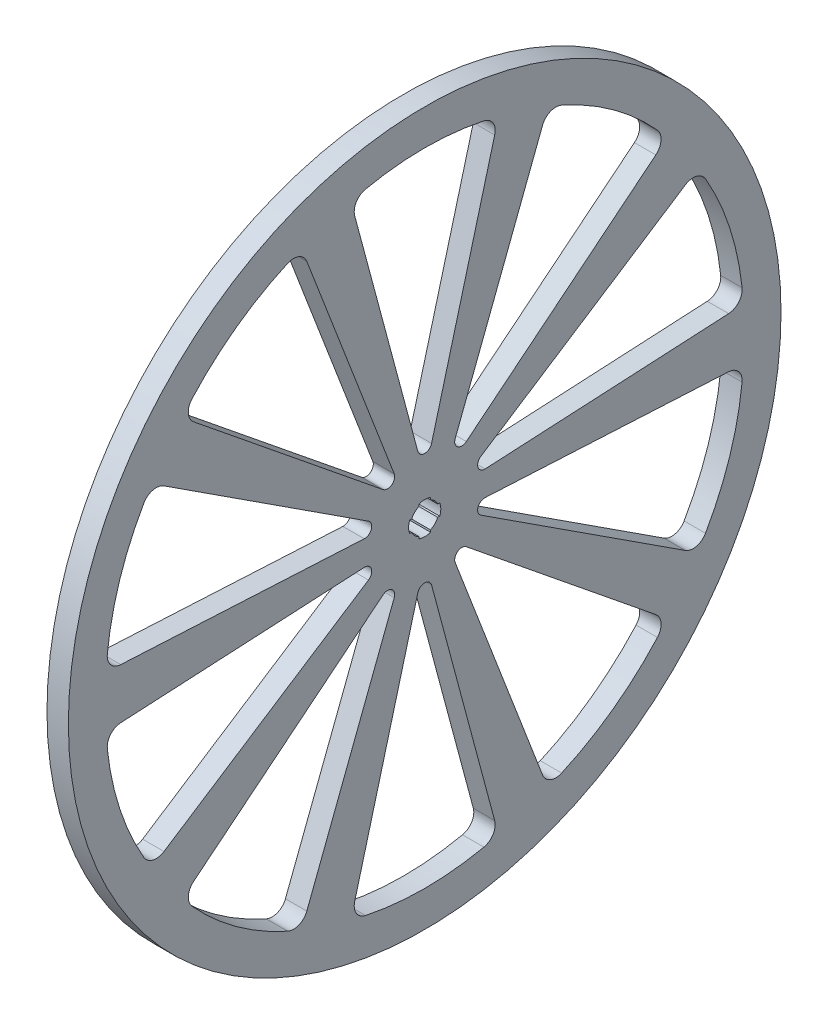
SolidWorks part; units mm, degrees
ref_plane "Front Plane" through (0, 0, 0) normal (0, 0, 1) x (1, 0, 0)
ref_plane "Top Plane" through (0, 0, 0) normal (0, 1, 0) x (1, 0, 0)
ref_plane "Right Plane" through (0, 0, 0) normal (1, 0, 0) x (0, 0, -1)
sketch "Sketch1" plane through (0, 0, 0) normal (1, 0, 0) x (0, 0, -1)
  circle A0 centre (0, 0) radius 50
  dimension "D1" = 100
extrude "Boss-Extrude1" add sketch "Sketch1" along normal blind 3
sketch "Sketch2" plane through (3, 0, 0) normal (1, 0, 0) x (0, 0, -1)
  circle A0 centre (0, 0) radius 2
  dimension "D1" = 4
extrude "Cut-Extrude1" cut sketch "Sketch2" against normal blind 3
sketch "Sketch3" plane through (3, 0, 0) normal (1, 0, 0) x (0, 0, -1)
  line L0 (0, 5) -> (0, 45) construction
  line L1 (0.9659, 8.6049) -> (9.8215, 41.6543)
  line L2 (-0.9659, 8.6049) -> (-9.8215, 41.6543)
  circle A0 centre (0, 0) radius 50 construction
  arc A2 (8.3049, 44.1284) -> (-8.3049, 44.1284) centre (0, 5) ccw
  arc A3 (9.8215, 41.6543) -> (8.3049, 44.1284) centre (7.8896, 42.1719) ccw
  arc A4 (-9.8215, 41.6543) -> (-8.3049, 44.1284) centre (-7.8896, 42.1719) cw
  arc A5 (-0.9659, 8.6049) -> (0.9659, 8.6049) centre (0, 8.8637) ccw
  point P11 (10.3528, 43.637)
  point P14 (-10.3528, 43.637)
  dimension "D7" = 2
  dimension "D8" = 1
  dimension "D1" = 5
  dimension "D2" = 45
  dimension "D3" = 15
  dimension "D4" = 40
  dimension "D5" = 15
  dimension "D6" = 40
extrude "Cut-Extrude2" cut sketch "Sketch3" against normal blind 3
pattern_circular "CirPattern2" count 10 over 360 about axis through (0, 0, 0) along (1, 0, 0) of "Cut-Extrude2"
sketch "Sketch4" plane through (3, 0, 0) normal (1, 0, 0) x (0, 0, -1)
  line L0 (-2.1099, 0.81) -> (-0.81, 0.81)
  line L1 (2.1099, -0.81) -> (-2.1099, -0.81) construction
  line L2 (2.1099, -0.81) -> (2.1099, 0.81) construction
  line L3 (2.1099, 0.81) -> (-2.1099, 0.81) construction
  line L4 (-2.1099, -0.81) -> (-2.1099, 0.81) construction
  line L5 (2.1099, -0.81) -> (-2.1099, 0.81) construction
  line L6 (2.1099, 0.81) -> (-2.1099, -0.81) construction
  line L7 (-0.81, -2.1099) -> (0.81, -2.1099) construction
  line L8 (-0.81, -2.1099) -> (-0.81, 2.1099) construction
  line L9 (-0.81, 2.1099) -> (0.81, 2.1099) construction
  line L10 (0.81, -2.1099) -> (0.81, 2.1099) construction
  line L11 (-0.81, -2.1099) -> (0.81, 2.1099) construction
  line L12 (-0.81, 2.1099) -> (0.81, -2.1099) construction
  line L13 (-0.81, 0.81) -> (-0.81, 2.1099)
  line L14 (0.81, 2.1099) -> (0.81, 0.81)
  line L15 (0.81, 0.81) -> (2.1099, 0.81)
  line L16 (2.1099, -0.81) -> (0.81, -0.81)
  line L17 (0.81, -0.81) -> (0.81, -2.1099)
  line L18 (-0.81, -2.1099) -> (-0.81, -0.81)
  line L19 (-0.81, -0.81) -> (-2.1099, -0.81)
  circle A0 centre (0, 0) radius 2.26 construction
  spline S0 degree 2 poles (-2.1099, -0.81) (-2.4101, 0) (-2.1099, 0.81) knots 0 0 0 1 1 1
  spline S1 degree 2 poles (-0.81, 2.1099) (0, 2.4101) (0.81, 2.1099) knots 0 0 0 1 1 1
  spline S2 degree 2 poles (2.1099, 0.81) (2.4101, 0) (2.1099, -0.81) knots 0 0 0 1 1 1
  spline S3 degree 2 poles (0.81, -2.1099) (0, -2.4101) (-0.81, -2.1099) knots 0 0 0 1 1 1
  dimension "D1" = 4.52
  dimension "D2" = 1.62
  dimension "D3" = 1.62
extrude "Cut-Extrude3" cut sketch "Sketch4" against normal blind 10
equation "\"D1@Sketch4\"=4.70mm-0.18"
